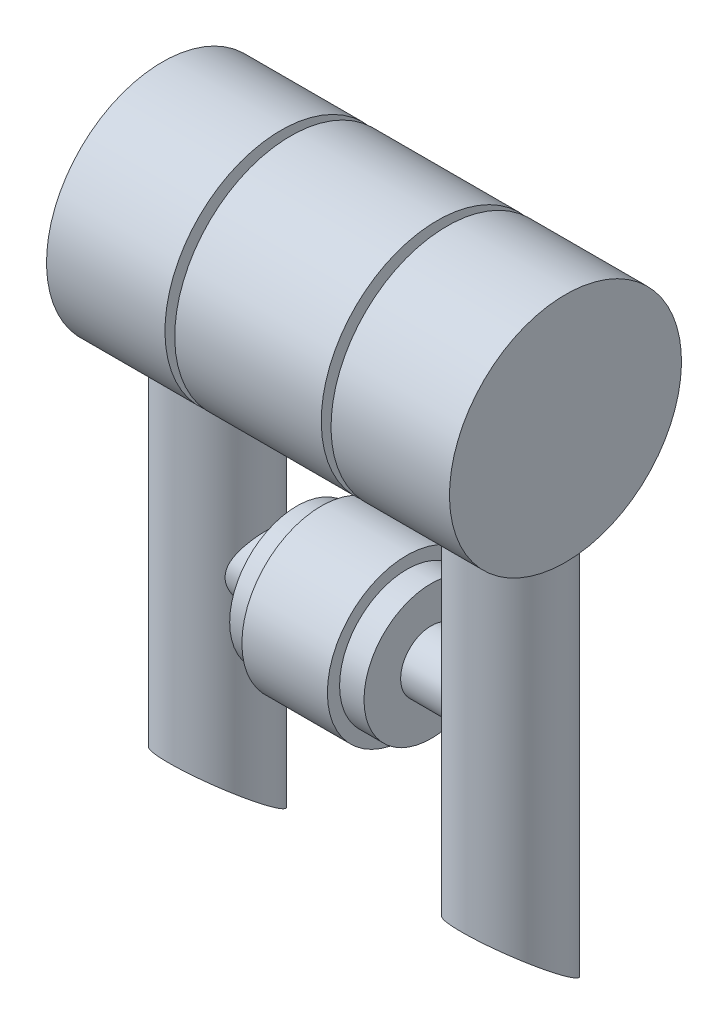
SolidWorks part; units mm, degrees
ref_plane "Спереди" through (0, 0, 0) normal (0, 0, 1) x (1, 0, 0)
ref_plane "Сверху" through (0, 0, 0) normal (0, 1, 0) x (1, 0, 0)
ref_plane "Справа" through (0, 0, 0) normal (1, 0, 0) x (0, 0, -1)
sketch "Эскиз4" plane through (0, 0, 0) normal (0, 0, 1) x (1, 0, 0)
  line L0 (-16.5, 0) -> (-16.5, 9.5)
  line L1 (-16.5, 9.5) -> (-6.8, 9.5)
  line L2 (-6.8, 9.5) -> (-6.8, 8)
  line L3 (-6.8, 8) -> (-6, 8)
  line L4 (-6, 8) -> (-6, 9.5)
  line L5 (-6, 9.5) -> (6, 9.5)
  line L6 (0, -5.5164) -> (0, 20.1723) construction
  line L7 (6, 8) -> (6, 9.5)
  line L8 (6.8, 8) -> (6, 8)
  line L9 (6.8, 9.5) -> (6.8, 8)
  line L10 (16.5, 9.5) -> (6.8, 9.5)
  line L11 (16.5, 0) -> (16.5, 9.5)
  line L12 (-16.5, 0) -> (16.5, 0)
  point P11 (0, 9.5)
  dimension "D1" = 0.8
  dimension "D2" = 16.5
  dimension "D3" = 6
  dimension "D4" = 9.7
  dimension "D5" = 8
  dimension "D6" = 9.5
revolve "Повернуть1" add sketch "Эскиз4" angle 360 about L12
sketch "Эскиз5" plane through (0, 0, 0) normal (0, 1, 0) x (1, 0, 0)
  line L0 (0, -12.4299) -> (0, 13.9114) construction
  circle A0 centre (-12, 0) radius 4
  circle A1 centre (12, 0) radius 4
  dimension "D1" = 8
  dimension "D2" = 24
  dimension "D3" = 12
extrude "Бобышка-Вытянуть3" add sketch "Эскиз5" against normal blind 42
sketch "Эскиз6" plane through (0, 0, 0) normal (1, 0, 0) x (0, 0, -1)
  line L0 (4, -42) -> (-4, -35.9716)
  line L2 (-4, -8.6168) -> (-4, -42) construction
  line L3 (-4, -35.9716) -> (-4, -42)
  line L4 (-4, -42) -> (4, -42)
  dimension "D1" = 37
extrude "Вырез-Вытянуть2" cut sketch "Эскиз6" against normal through all and the other way through all
sketch "Эскиз7" plane through (0, 0, 0) normal (1, 0, 0) x (0, 0, -1)
  circle A0 centre (0, -22) radius 2.5
  dimension "D1" = 22
extrude "Бобышка-Вытянуть4" add sketch "Эскиз7" along normal blind 12 and the other way blind 12
sketch "Эскиз8" plane through (0, 0, 0) normal (0, 0, 1) x (1, 0, 0)
  line L0 (-20.2265, -22) -> (22.2611, -22) construction
  line L1 (-5.5, -22) -> (-5.5, -16.5)
  line L2 (-5.5, -16.5) -> (-3.5, -16.5)
  line L3 (-3.5, -16.5) -> (-3.5, -15.5)
  line L4 (-3.5, -15.5) -> (3.5, -15.5)
  line L5 (3.5, -15.5) -> (3.5, -16.5)
  line L6 (3.5, -16.5) -> (5.5, -16.5)
  line L7 (5.5, -16.5) -> (5.5, -22)
  line L8 (5.5, -22) -> (-5.5, -22)
  dimension "D1" = 22
  dimension "D2" = 7
  dimension "D3" = 5.5
  dimension "D4" = 6.5
  dimension "D5" = 3.5
  dimension "D6" = 5.5
revolve "Повернуть2" add sketch "Эскиз8" angle 360 about L0
equation "\"D2\"= 24 / 2"
